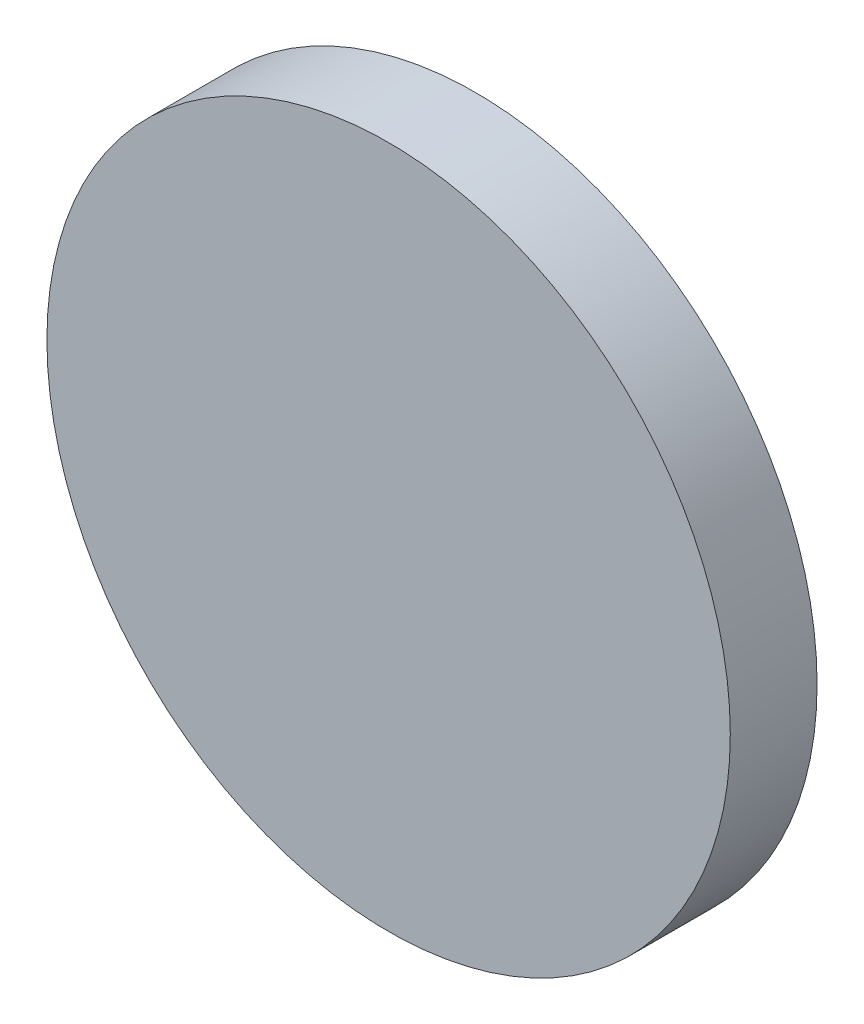
SolidWorks part; units mm, degrees
ref_plane "Front Plane" through (0, 0, 0) normal (0, 0, 1) x (1, 0, 0)
ref_plane "Top Plane" through (0, 0, 0) normal (0, 1, 0) x (1, 0, 0)
ref_plane "Right Plane" through (0, 0, 0) normal (1, 0, 0) x (0, 0, -1)
sketch "Sketch1" plane through (0, 0, 0) normal (0, 0, 1) x (1, 0, 0)
  circle A0 centre (0, 0) radius 25
  point P2 (0, 0)
  dimension "D1" = 50
extrude "Boss-Extrude1" add sketch "Sketch1" along normal blind 6.35 contours A0
